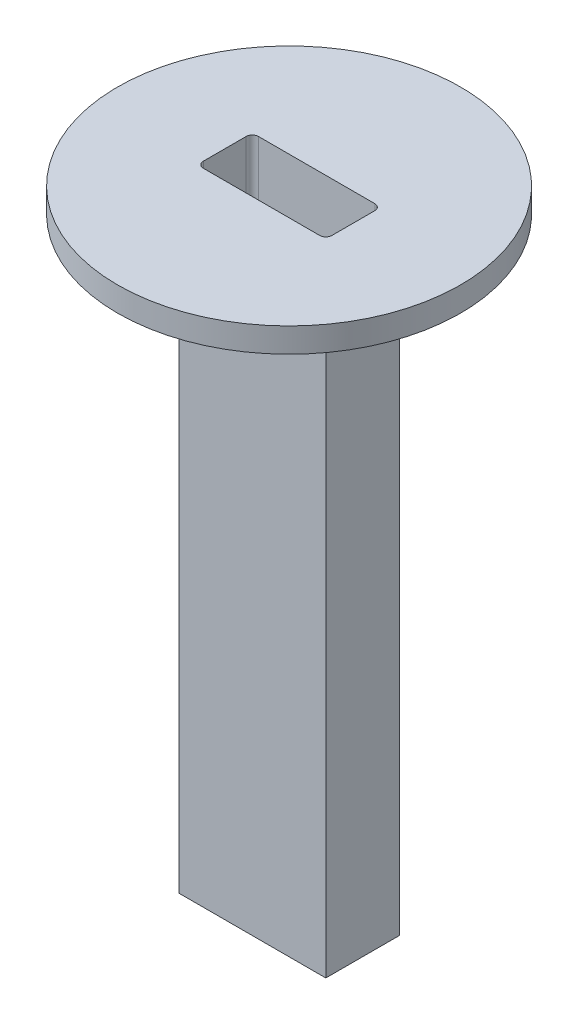
SolidWorks part; units mm, degrees
ref_plane "Front Plane" through (0, 0, 0) normal (0, 0, 1) x (1, 0, 0)
ref_plane "Top Plane" through (0, 0, 0) normal (0, 1, 0) x (1, 0, 0)
ref_plane "Right Plane" through (0, 0, 0) normal (1, 0, 0) x (0, 0, -1)
sketch "Sketch1" plane through (0, 0, 0) normal (0, 1, 0) x (1, 0, 0)
  circle A0 centre (0, 0) radius 88.9
extrude "Boss-Extrude1" add sketch "Sketch1" along normal blind 12.7
sketch "Sketch2" plane through (0, 0, 0) normal (0, -1, 0) x (1, 0, 0)
  line L1 (-38.1, 19.05) -> (38.1, 19.05)
  line L2 (-38.1, 19.05) -> (-38.1, -19.05)
  line L3 (-38.1, -19.05) -> (38.1, -19.05)
  line L4 (38.1, 19.05) -> (38.1, -19.05)
  dimension "D1" = 38.1
  dimension "D2" = 76.2
  dimension "D3" = 38.1
  dimension "D4" = 19.05
extrude "Boss-Extrude2" add sketch "Sketch2" along normal blind 314.325
sketch "Sketch3" plane through (0, 12.7, 0) normal (0, 1, 0) x (1, 0, 0)
  line L1 (-30.1625, 14.2875) -> (30.1625, 14.2875)
  line L2 (-33.3375, 11.1125) -> (-33.3375, -11.1125)
  line L3 (-30.1625, -14.2875) -> (30.1625, -14.2875)
  line L4 (33.3375, 11.1125) -> (33.3375, -11.1125)
  arc A0 (-30.1625, 14.2875) -> (-33.3375, 11.1125) centre (-30.1625, 11.1125) ccw
  arc A1 (33.3375, 11.1125) -> (30.1625, 14.2875) centre (30.1625, 11.1125) ccw
  arc A2 (33.3375, -11.1125) -> (30.1625, -14.2875) centre (30.1625, -11.1125) cw
  arc A3 (-33.3375, -11.1125) -> (-30.1625, -14.2875) centre (-30.1625, -11.1125) ccw
  point P7 (-33.3375, 14.2875)
  point P10 (33.3375, 14.2875)
  point P15 (-33.3375, -14.2875)
  dimension "D5" = 3.175
  dimension "D6" = 3.175
  dimension "D7" = 3.175
  dimension "D8" = 3.175
  dimension "D1" = 28.575
  dimension "D2" = 66.675
  dimension "D3" = 33.3375
  dimension "D4" = 14.2875
extrude "Cut-Extrude1" cut sketch "Sketch3" against normal blind 317.5
